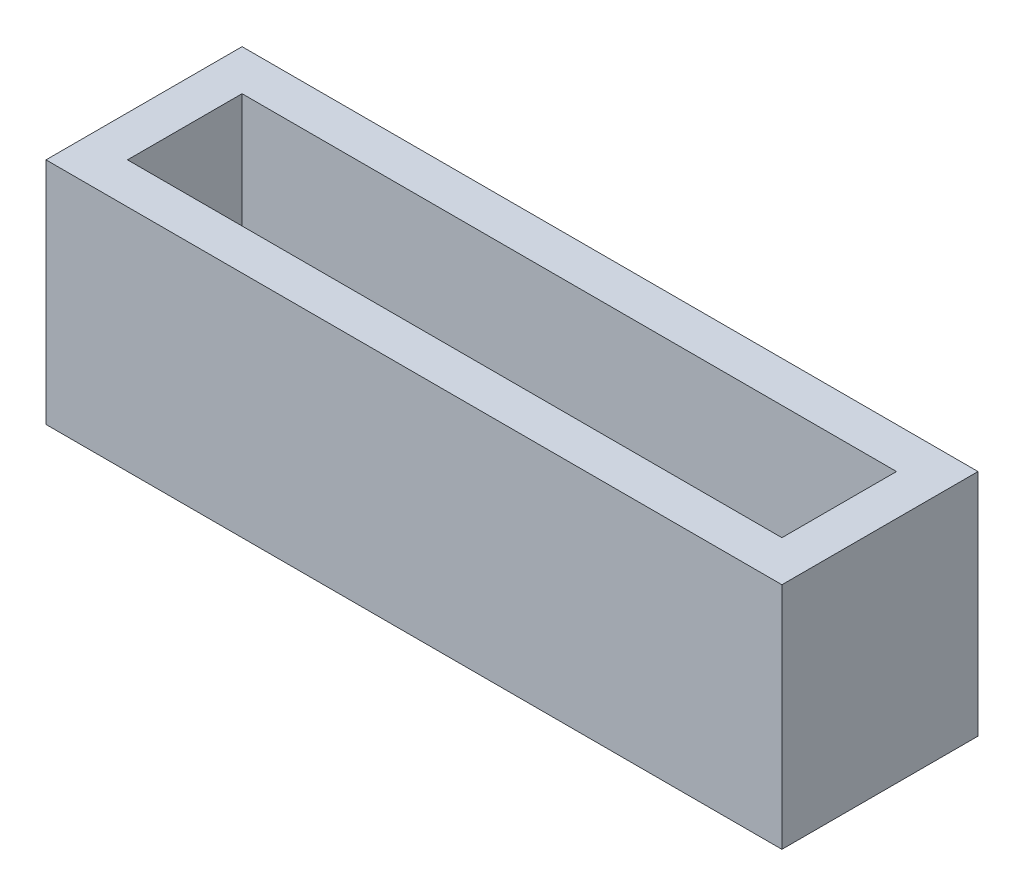
SolidWorks part; units mm, degrees
ref_plane "Front Plane" through (0, 0, 0) normal (0, 0, 1) x (1, 0, 0)
ref_plane "Top Plane" through (0, 0, 0) normal (0, 1, 0) x (1, 0, 0)
ref_plane "Right Plane" through (0, 0, 0) normal (1, 0, 0) x (0, 0, -1)
sketch "Sketch1" plane through (0, 0, 0) normal (0, 1, 0) x (1, 0, 0)
  line L0 (-7.3266, 5.4061) -> (21.5734, 5.4061)
  line L1 (-5.7266, 3.8061) -> (19.9734, 3.8061)
  line L2 (-5.7266, 3.8061) -> (-5.7266, -0.6939)
  line L3 (-5.7266, -0.6939) -> (19.9734, -0.6939)
  line L4 (19.9734, 3.8061) -> (19.9734, -0.6939)
  line L5 (21.5734, 5.4061) -> (21.5734, -2.2939)
  line L6 (-7.3266, -2.2939) -> (21.5734, -2.2939)
  line L7 (-7.3266, 5.4061) -> (-7.3266, -2.2939)
  point P8 (0, 0)
  point P9 (0, 0)
  point P10 (0, 0)
  dimension "D1" = 25.7
  dimension "D2" = 4.5
  dimension "D3" = 1.6
extrude "Boss-Extrude1" add sketch "Sketch1" along normal blind 9 contours L0 L7 L6 L5 L1 L4 L3 L2
